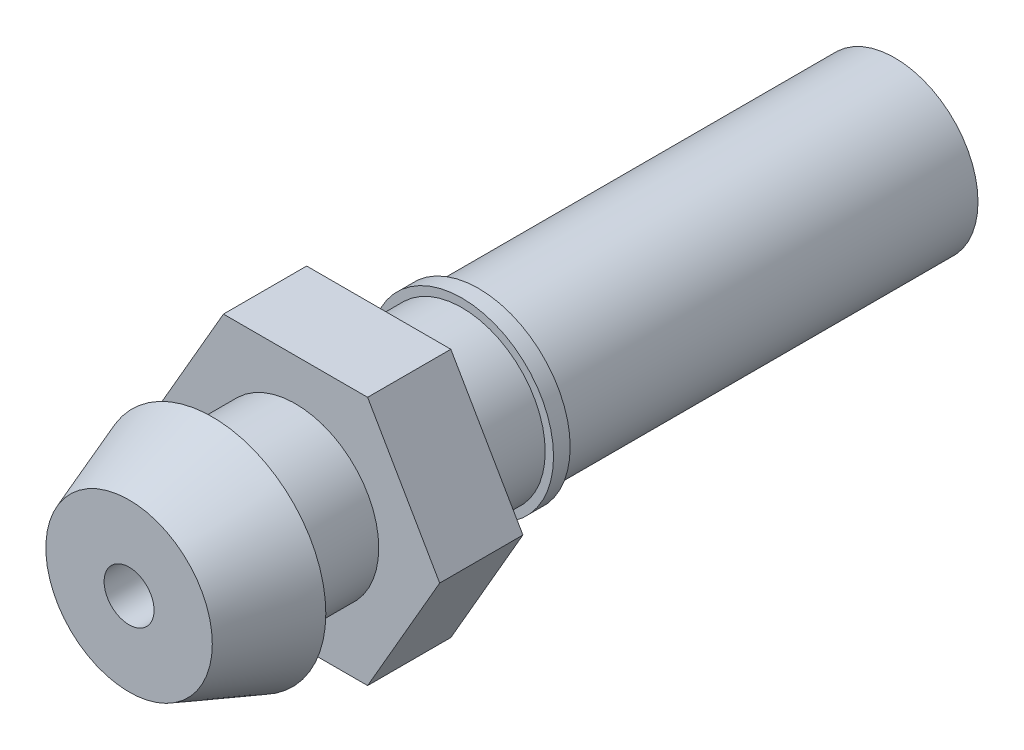
SolidWorks part; units mm, degrees
material "Plain Carbon Steel"
ref_plane "Front Plane" through (0, 0, 0) normal (0, 0, 1) x (1, 0, 0)
ref_plane "Top Plane" through (0, 0, 0) normal (0, 1, 0) x (1, 0, 0)
ref_plane "Right Plane" through (0, 0, 0) normal (1, 0, 0) x (0, 0, -1)
sketch "Sketch1" plane through (0, 0, 0) normal (0, 0, 1) x (1, 0, 0)
  circle A0 centre (0, 0) radius 1.27
  dimension "D1" = 2.54
extrude "Boss-Extrude1" add sketch "Sketch1" along normal blind 6.35
sketch "Sketch2" plane through (0, 0, 6.35) normal (0, 0, 1) x (1, 0, 0)
  circle A0 centre (0, 0) radius 1.397
  dimension "D1" = 2.794
extrude "Boss-Extrude2" add sketch "Sketch2" along normal blind 0.254
sketch "Sketch3" plane through (0, 0, 6.604) normal (0, 0, 1) x (1, 0, 0)
  circle A0 centre (0, 0) radius 1.27
  dimension "D1" = 2.54
extrude "Boss-Extrude3" add sketch "Sketch3" along normal blind 1.27
sketch "Sketch4" plane through (0, 0, 7.874) normal (0, 0, 1) x (1, 0, 0)
  line L1 (2.1997, 0) -> (1.0999, 1.905)
  line L2 (1.0999, 1.905) -> (-1.0999, 1.905)
  line L3 (-1.0999, 1.905) -> (-2.1997, 0)
  line L4 (-2.1997, 0) -> (-1.0999, -1.905)
  line L5 (-1.0999, -1.905) -> (1.0999, -1.905)
  line L6 (1.0999, -1.905) -> (2.1997, 0)
  circle A0 centre (0, 0) radius 1.905 construction
  dimension "D1" = 3.81
extrude "Boss-Extrude4" add sketch "Sketch4" along normal blind 1.27
sketch "Sketch5" plane through (0, 0, 9.144) normal (0, 0, 1) x (1, 0, 0)
  circle A0 centre (0, 0) radius 1.27
  dimension "D1" = 2.54
extrude "Boss-Extrude5" add sketch "Sketch5" along normal blind 1.27
sketch "Sketch6" plane through (0, 0, 10.414) normal (0, 0, 1) x (1, 0, 0)
  circle A0 centre (0, 0) radius 1.27
  dimension "D1" = 2.54
extrude "Boss-Extrude6" add sketch "Sketch6" along normal blind 1.27 separate body
draft "Draft3" type of draft neutral plane draft angle 20 faces to draft 1 face at (1.27, 0, 11.684) neutral plane through (0, 0, 11.684) neutral plane normal (0, 0, 1) parameters "D1"=20
sketch "Sketch7" plane through (0, 0, 11.684) normal (0, 0, 1) x (1, 0, 0)
  circle A0 centre (0, 0) radius 0.381
  dimension "D1" = 0.762
extrude "Cut-Extrude1" cut sketch "Sketch7" against normal through all
